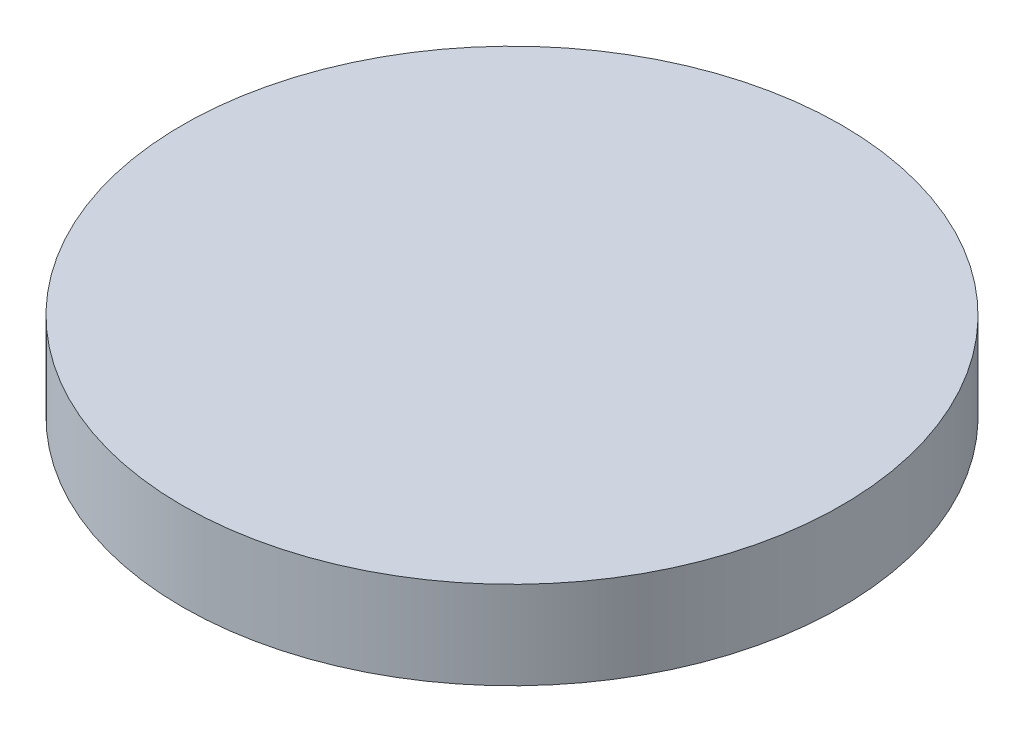
SolidWorks part; units mm, degrees
ref_plane "Front Plane" through (0, 0, 0) normal (0, 0, 1) x (1, 0, 0)
ref_plane "Top Plane" through (0, 0, 0) normal (0, 1, 0) x (1, 0, 0)
ref_plane "Right Plane" through (0, 0, 0) normal (1, 0, 0) x (0, 0, -1)
sketch "Sketch1" plane through (0, 0, 0) normal (0, 1, 0) x (1, 0, 0)
  circle A0 centre (0, 0) radius 7.5
  dimension "D1" = 15
extrude "Boss-Extrude1" add sketch "Sketch1" along normal blind 2
equation "\"PawnHeight\"= 2mm"
equation "\"MagDiam\"= 12mm"
equation "\"MagThickness\"= 3mm"
equation "\"KnightHeight\"= 3mm"
equation "\"RookHeight\"= 4mm"
equation "\"BishopHeight\"= 5mm"
equation "\"QueenHeight\"= 6mm"
equation "\"KingHeight\"= 7mm"
equation "\"WeightOuterDiam\"= 25mm"
equation "\"WeightInnerDiam\"= \"MagDiam\" + 0.3mm"
equation "\"WeightHeight\"= 9mm"
equation "\"D1@Sketch1\"=15mm"
equation "\"D1@Boss-Extrude1\"=2mm"
